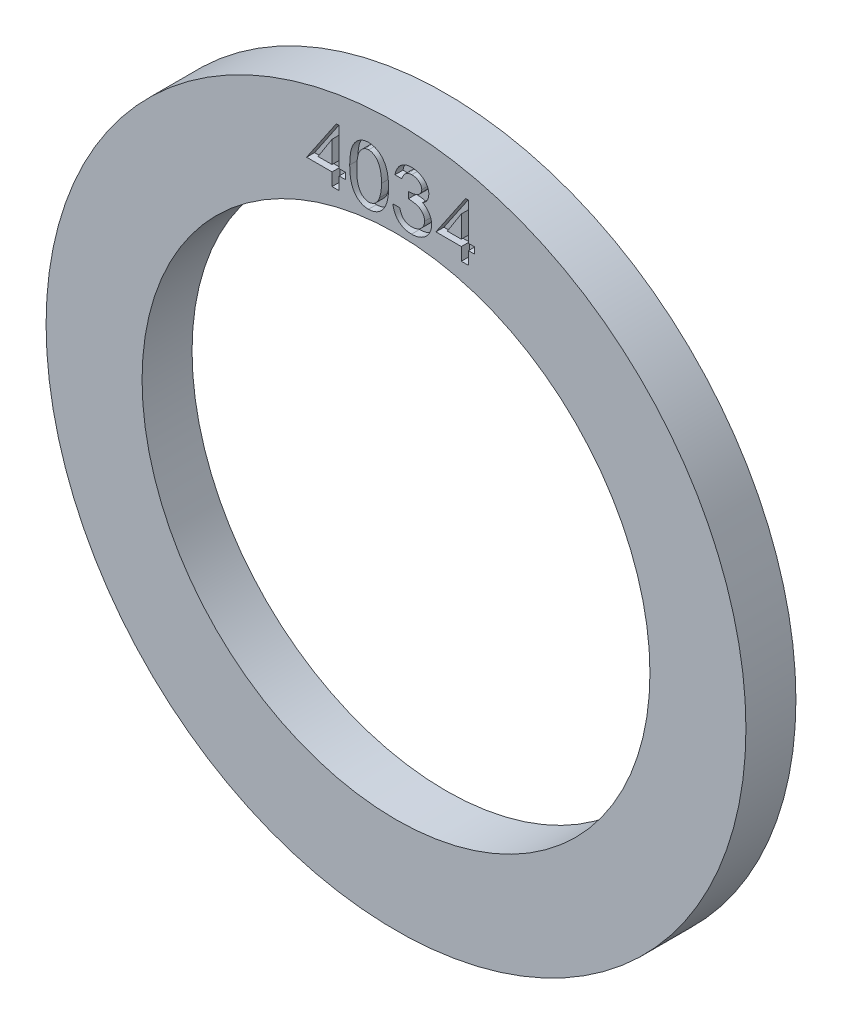
SolidWorks part; units mm, degrees
material "Nylon 101"
ref_plane "Front Plane" through (0, 0, 0) normal (0, 0, 1) x (1, 0, 0)
ref_plane "Top Plane" through (0, 0, 0) normal (0, 1, 0) x (1, 0, 0)
ref_plane "Right Plane" through (0, 0, 0) normal (1, 0, 0) x (0, 0, -1)
sketch "Sketch1" plane through (0, 0, 0) normal (0, 0, 1) x (1, 0, 0)
  circle A0 centre (0, 0) radius 16.129
  circle A1 centre (0, 0) radius 22.225
  dimension "D1" = 32.258
  dimension "D2" = 44.45
extrude "Boss-Extrude1" add sketch "Sketch1" along normal mid plane 3.175
sketch "Sketch2" plane through (0, 0, 1.5875) normal (0, 0, 1) x (1, 0, 0)
  text T0 "<b>4034</b>" font "Century Gothic" height 3.5
  point P1 (-5.8128, 16.6613)
extrude "Cut-Extrude2" cut sketch "Sketch2" against normal blind 0.508
